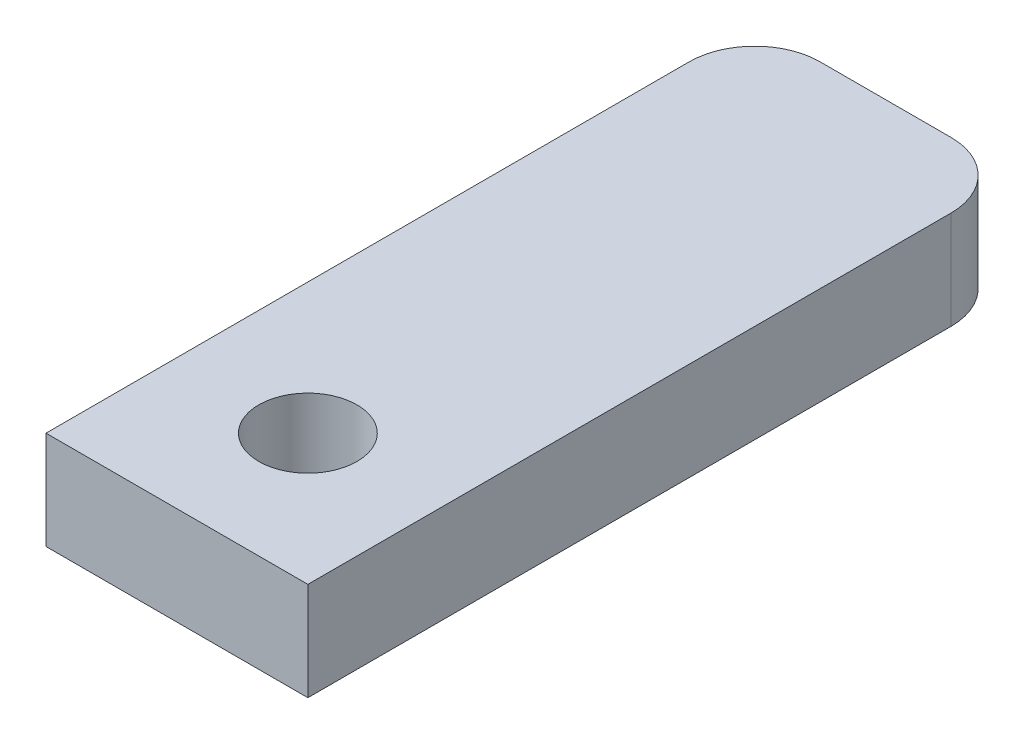
SolidWorks part; units mm, degrees
ref_plane "Front Plane" through (0, 0, 0) normal (0, 0, 1) x (1, 0, 0)
ref_plane "Top Plane" through (0, 0, 0) normal (0, 1, 0) x (1, 0, 0)
ref_plane "Right Plane" through (0, 0, 0) normal (1, 0, 0) x (0, 0, -1)
sketch "Sketch1" plane through (0, 0, 0) normal (0, 1, 0) x (1, 0, 0)
  line L1 (4, -10.8239) -> (-4, -10.8239)
  line L2 (4, -10.8239) -> (4, 8.8239)
  line L3 (2, 10.8239) -> (-2, 10.8239)
  line L4 (-4, -10.8239) -> (-4, 8.8239)
  line L5 (4, -10.8239) -> (-4, 10.8239) construction
  line L6 (4, 10.8239) -> (-4, -10.8239) construction
  circle A0 centre (0, -6.8239) radius 1.5
  arc A1 (-2, 10.8239) -> (-4, 8.8239) centre (-2, 8.8239) ccw
  arc A2 (4, 8.8239) -> (2, 10.8239) centre (2, 8.8239) ccw
  point P0 (0, 0)
  dimension "D2" = 3
  dimension "D3" = 4
  dimension "D4" = 2
  dimension "D1" = 8
extrude "Boss-Extrude1" add sketch "Sketch1" along normal blind 3
